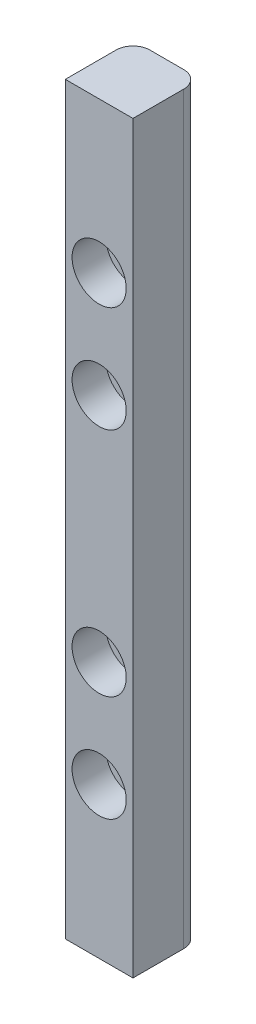
SolidWorks part; units mm, degrees
ref_plane "Front Plane" through (0, 0, 0) normal (0, 0, 1) x (1, 0, 0)
ref_plane "Top Plane" through (0, 0, 0) normal (0, 1, 0) x (1, 0, 0)
ref_plane "Right Plane" through (0, 0, 0) normal (1, 0, 0) x (0, 0, -1)
sketch "Sketch2" plane through (0, 0, 0) normal (0, 0, 1) x (1, 0, 0)
  line L0 (0, 0) -> (0, 110)
  line L1 (0, 110) -> (10, 110)
  line L2 (10, 110) -> (10, 0)
  line L3 (10, 0) -> (0, 0)
extrude "Boss-Extrude1" add sketch "Sketch2" along normal blind 10
sketch "Sketch3" plane through (0, 0, 10) normal (0, 0, 1) x (1, 0, 0)
  circle A2 centre (5, 87.7319) radius 4
  circle A3 centre (5, 72.0775) radius 4
  circle A7 centre (5, 37.9225) radius 4
  circle A8 centre (5, 22.2681) radius 4
extrude "Cut-Extrude1" cut sketch "Sketch3" against normal blind 5
fillet "Fillet1" radius 2.5 2 edges at (0, 55, 0) (10, 55, 0)
